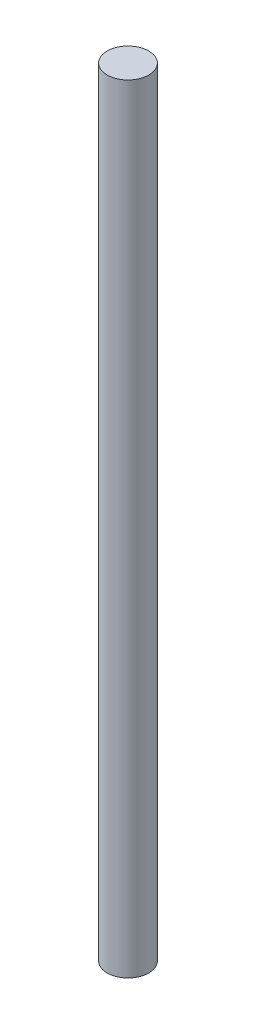
SolidWorks part; units mm, degrees
ref_plane "Front Plane" through (0, 0, 0) normal (0, 0, 1) x (1, 0, 0)
ref_plane "Top Plane" through (0, 0, 0) normal (0, 1, 0) x (1, 0, 0)
ref_plane "Right Plane" through (0, 0, 0) normal (1, 0, 0) x (0, 0, -1)
sketch "Sketch1" plane through (0, 0, 0) normal (0, 1, 0) x (1, 0, 0)
  circle A0 centre (0, 0) radius 4.95
  dimension "D1" = 9.9
extrude "Boss-Extrude1" add sketch "Sketch1" along normal blind 185
